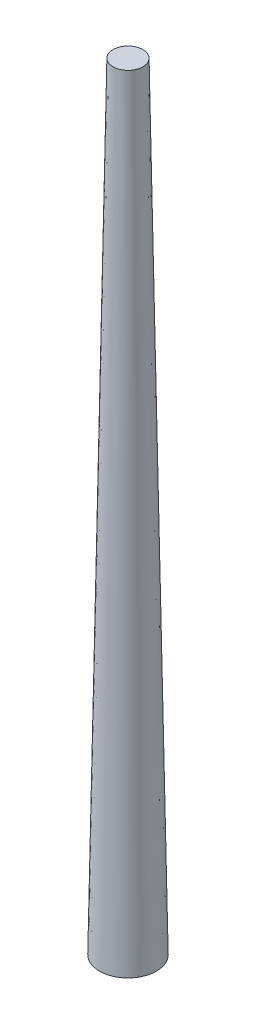
SolidWorks part; units mm, degrees
material "PS Średni/wysoki przepływ"
ref_plane "Płaszczyzna przednia" through (0, 0, 0) normal (0, 0, 1) x (1, 0, 0)
ref_plane "Płaszczyzna górna" through (0, 0, 0) normal (0, 1, 0) x (1, 0, 0)
ref_plane "Płaszczyzna prawa" through (0, 0, 0) normal (1, 0, 0) x (0, 0, -1)
sketch "Szkic1" plane through (0, 0, 0) normal (0, 0, 1) x (1, 0, 0)
  line L0 (0, 78) -> (0, 0) construction
  line L1 (0, 0) -> (-2.8615, 0)
  line L2 (-2.8615, 0) -> (-1.5, 78)
  line L3 (-1.5, 78) -> (0, 78)
  line L4 (0, 78) -> (0, 0)
  dimension "D4" = 1
  dimension "D1" = 1.5
  dimension "D3" = 78
revolve "Obrót1" add sketch "Szkic1" angle 360 about L4
